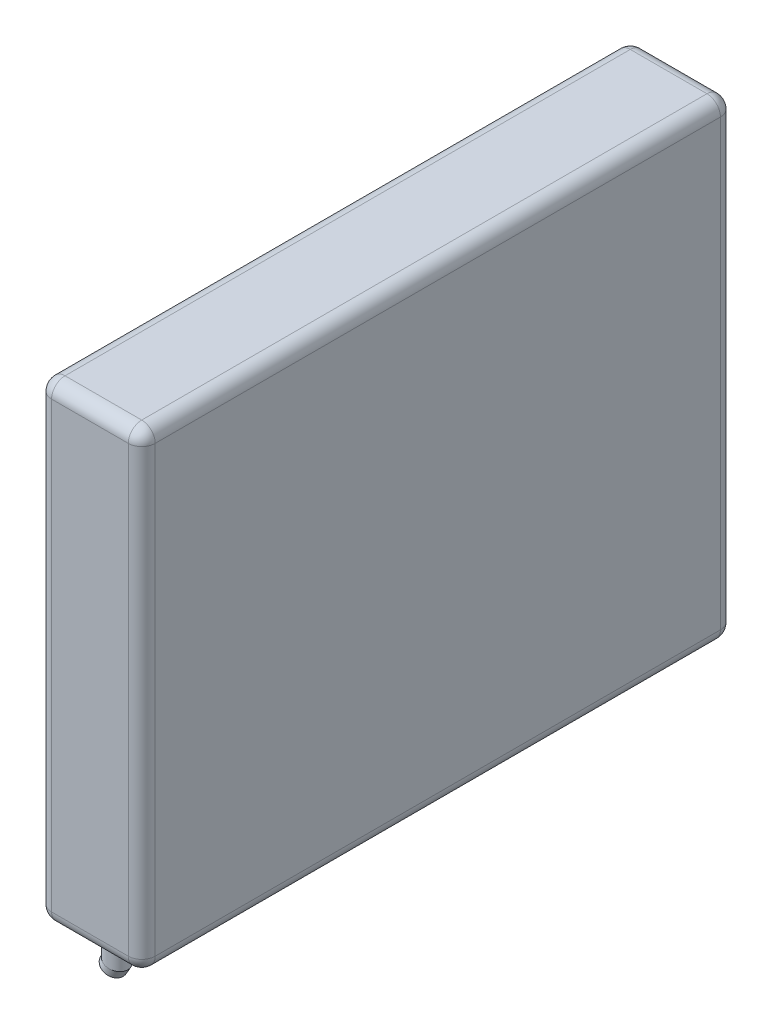
SolidWorks part; units mm, degrees
ref_plane "Front Plane" through (0, 0, 0) normal (0, 0, 1) x (1, 0, 0)
ref_plane "Top Plane" through (0, 0, 0) normal (0, 1, 0) x (1, 0, 0)
ref_plane "Right Plane" through (0, 0, 0) normal (1, 0, 0) x (0, 0, -1)
sketch "Sketch1" plane through (0, 0, 0) normal (1, 0, 0) x (0, 0, -1)
  line L0 (0, 8.75) -> (0, -8.75) construction
  line L1 (-11, -8.75) -> (11, -8.75)
  line L2 (-11, -8.75) -> (-11, 8.75)
  line L3 (-11, 8.75) -> (11, 8.75)
  line L4 (11, -8.75) -> (11, 8.75)
  line L5 (-11, -8.75) -> (11, 8.75) construction
  line L6 (-11, 8.75) -> (11, -8.75) construction
  point P0 (0, 0)
  point P6 (-10, -8.75)
  dimension "D1" = 17.5
  dimension "D2" = 22
  dimension "D3" = 20
extrude "Boss-Extrude1" add sketch "Sketch1" along normal mid plane 3.85
sketch "Sketch2" plane through (0, -8.75, 0) normal (0, -1, 0) x (1, 0, 0)
  circle A0 centre (0, 10) radius 0.4064
  dimension "D1" = 0.8128
ref_plane "Plane1" through (0, 0, 10) normal (0, 0, 1) x (1, 0, 0)
sketch "Sketch3" plane through (0, 0, 10) normal (0, 0, 1) x (1, 0, 0)
  line L0 (0, -8.75) -> (0, -9.5882)
  line L1 (-0.4064, -8.75) -> (0.4064, -8.75) construction
  line L2 (0, -9.5882) -> (-0.1183, -9.7931)
  line L3 (-0.1183, -9.7931) -> (0.7554, -10.2975) construction
  dimension "D1" = 30
sweep "Sweep1" add profiles "Sketch2" path "Sketch3"
fillet "Fillet1" radius 0.5 12 edges at (-1.925, 0, -11) (-1.925, 8.75, 0) (-1.925, 0, 11) (-1.925, -8.75, 0) (1.925, 0, -11) (1.925, 8.75, 0) (1.925, 0, 11) (1.925, -8.75, 0) (0, -8.75, -11) (0, -8.75, 11) (0, 8.75, -11) (0, 8.75, 11)
mirror "Mirror1" about plane through (0, 0, 0) normal (0, 0, 1) of "Sweep1"
